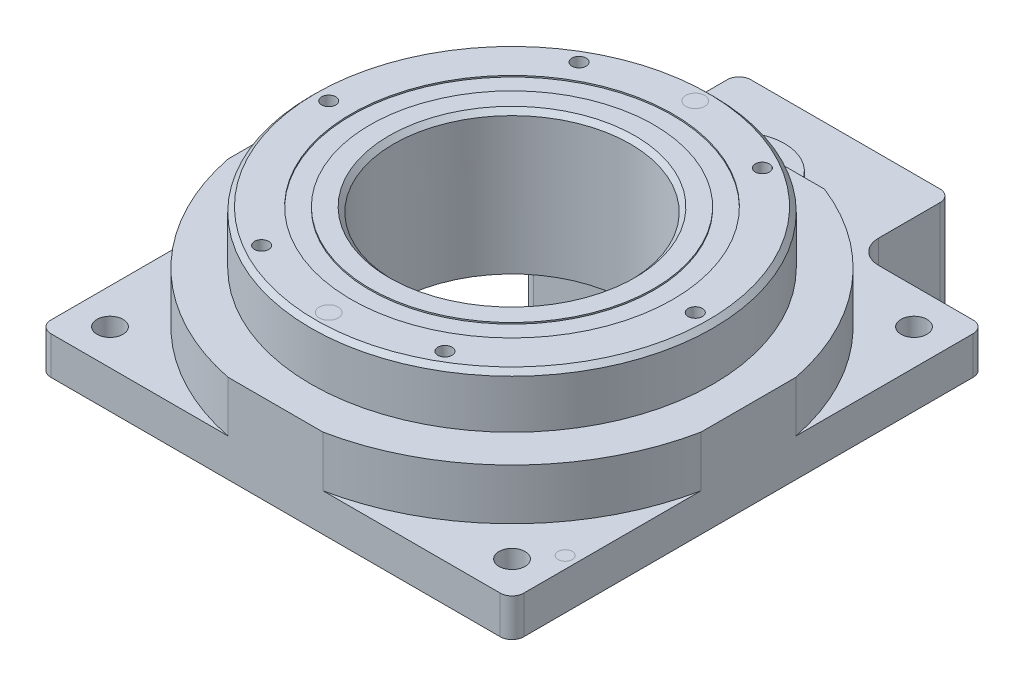
SolidWorks part; units mm, degrees
ref_plane "前视基准面" through (0, 0, 0) normal (0, 0, 1) x (1, 0, 0)
ref_plane "上视基准面" through (0, 0, 0) normal (0, 1, 0) x (1, 0, 0)
ref_plane "右视基准面" through (0, 0, 0) normal (1, 0, 0) x (0, 0, -1)
sketch "草图1" plane through (0, 0, 0) normal (0, 0, 1) x (1, 0, 0)
  line L0 (0, 0) -> (0, 60) construction
  point P3 (85, 60)
  point P4 (50, 60)
  point P5 (0, -53)
  point P6 (0, 37.5)
  point P7 (85, 51.5)
  point P8 (0, 16)
  dimension "D1" = 60
  dimension "D2" = 170
  dimension "D3" = 100
  dimension "D4" = 53
  dimension "D5" = 37.5
  dimension "D6" = 8.5
  dimension "D7" = 16
sketch "草图3" plane through (0, 0, 0) normal (0, 1, 0) x (1, 0, 0)
  line L0 (-141, 45) -> (-141, -45)
  line L1 (100, 100) -> (-100, 100)
  line L2 (100, 100) -> (100, -100)
  line L3 (100, -100) -> (-100, -100)
  line L4 (-100, 100) -> (-100, -100)
  line L5 (100, 100) -> (-100, -100) construction
  line L6 (100, -100) -> (-100, 100) construction
  line L7 (0, 0) -> (-141, 0) construction
  line L8 (-141, 45) -> (-100, 45)
  line L9 (-141, -45) -> (-100, -45)
  line L10 (0, 0) -> (0, 100) construction
  line L11 (-95, 0) -> (-132.1231, 37.1231) construction
  line L12 (0, 0) -> (-100, 8.7489)
  line L13 (0, 0) -> (-100, -8.7489)
  circle A0 centre (85, -85) radius 5.5
  circle A2 centre (-95, 0) radius 52.5 construction
  circle A3 centre (-132.1231, 37.1231) radius 3
  circle A4 centre (-95, 0) radius 9.5
  circle A5 centre (-95, 0) radius 35
  point P0 (0, 0)
  point P12 (85, 85)
  point P13 (85, -85)
  point P14 (-85, 85)
  point P16 (-85, -85)
  point P17 (-102, 10)
  point P18 (-102, -10)
  point P22 (-95, 0)
  dimension "D7" = 11
  dimension "D10" = 105
  dimension "D11" = 45
  dimension "D12" = 6
  dimension "D13" = 19
  dimension "D14" = 70
  dimension "D1" = 200
  dimension "D2" = 241
  dimension "D3" = 90
  dimension "D4" = 85
  dimension "D5" = 20
  dimension "D6" = 39
  dimension "D9" = 95
  dimension "D15" = 10
sketch "草图5" plane through (0, 0, 0) normal (0, 1, 0) x (1, 0, 0)
  circle A0 centre (0, 0) radius 85
extrude "凸台-拉伸1" add sketch "草图5" along normal up to vertex (60 mm away) up to point (50, 60, 0)
sketch "草图6" plane through (0, 0, 0) normal (0, 1, 0) x (1, 0, 0)
  line L1 (100, 100) -> (-100, 100) construction
  line L2 (100, -100) -> (-100, -100) construction
  line L3 (20.0998, 100) -> (-20.0998, 100)
  line L4 (20.0998, -100) -> (-20.0998, -100)
  line L5 (100, 100) -> (100, -100) construction
  line L6 (100, 20.0998) -> (100, -20.0998)
  arc A0 (-20.0998, 100) -> (-20.0998, -100) centre (0, 0) ccw
  arc A1 (20.0998, -100) -> (100, -20.0998) centre (0, 0) ccw
  arc A2 (100, 20.0998) -> (20.0998, 100) centre (0, 0) ccw
  dimension "D1" = 204
extrude "凸台-拉伸2" add sketch "草图6" along normal up to vertex (37.5 mm away) up to point (0, 37.5, 0)
sketch "草图7" plane through (0, 0, 0) normal (0, 1, 0) x (1, 0, 0)
  line L0 (-141, 45) -> (-100, 45) construction
  line L1 (-141, 45) -> (-141, -45) construction
  line L2 (-141, -45) -> (-100, -45) construction
  line L3 (-100, 100) -> (-100, -100) construction
  line L4 (100, -100) -> (-100, -100) construction
  line L5 (100, 100) -> (100, -100) construction
  line L6 (100, 100) -> (-100, 100) construction
  line L7 (-141, 45) -> (-100, 45)
  line L8 (-141, 45) -> (-141, -45)
  line L9 (-141, -45) -> (-100, -45)
  line L10 (-100, 100) -> (-100, 45)
  line L11 (100, -100) -> (-100, -100)
  line L12 (100, 100) -> (100, -100)
  line L13 (100, 100) -> (-100, 100)
  line L14 (-100, -45) -> (-100, -100)
extrude "凸台-拉伸3" add sketch "草图7" along normal up to vertex (16 mm away) up to point (0, 16, 0)
sketch "草图8" plane through (0, 0, 0) normal (0, 1, 0) x (1, 0, 0)
  line L0 (0, 0) -> (-72.5, -95) construction
  line L2 (0, 0) -> (0, -95) construction
  circle A0 centre (85, -85) radius 5.5 construction
  circle A1 centre (85, -85) radius 5.5
  circle A2 centre (-72.5, -95) radius 3 construction
  dimension "D1" = 6
  dimension "D2" = 72.5
  dimension "D3" = 95
extrude "切除-拉伸1" cut sketch "草图8" along normal up to vertex (60 mm away) up to point (85, 60, 0)
pattern_circular "阵列(圆周)1" count 4 over 360 about axis through (0, 0, 0) along (0, 1, 0) of "切除-拉伸1"
sketch "草图11" plane through (0, 0, 0) normal (0, 1, 0) x (1, 0, 0)
  circle A0 centre (0, 0) radius 50
extrude "切除-拉伸5" cut sketch "草图11" along normal up to vertex (60 mm away) up to point (0, 60, 0)
sketch "草图12" plane through (0, 0, 0) normal (0, 1, 0) x (1, 0, 0)
  line L1 (-49, -45) -> (-141, -45)
  line L2 (-49, -45) -> (-49, 45)
  line L3 (-49, 45) -> (-141, 45)
  line L4 (-141, -45) -> (-141, 45)
  line L5 (-49, -45) -> (-141, 45) construction
  line L6 (-49, 45) -> (-141, -45) construction
  point P0 (-95, 0)
extrude "凸台-拉伸4" add sketch "草图12" against normal up to vertex (53 mm away) up to point (0, -53, 0)
fillet "圆角1" radius 5 4 edges at (-100, 8, -100) (100, 8, -100) (100, 8, 100) (-100, 8, 100)
fillet "圆角2" radius 5 4 edges at (-49, -26.5, -45) (-141, -18.5, -45) (-49, -26.5, 45) (-141, -18.5, 45)
sketch "草图14" plane through (0, 0, 0) normal (0, 1, 0) x (1, 0, 0)
  circle A0 centre (-95, 0) radius 20.25
  dimension "D1" = 40.5
extrude "凸台-拉伸5" add sketch "草图14" along normal blind 30
fillet "圆角3" radius 10 2 edges at (-100.0997, 23, -19.5973) (-100.0997, 23, 19.5973)
sketch "草图46" plane through (0, 0, 0) normal (0, 1, 0) x (1, 0, 0)
  line L0 (-95, 45) -> (-95, -45)
  line L1 (-141, 45) -> (-100, 45) construction
  line L2 (-141, -45) -> (-100, -45) construction
  line L3 (-95, 45) -> (-141, 45)
  line L4 (-141, 45) -> (-141, -45)
  line L5 (-141, -45) -> (-95, -45)
extrude "切除-拉伸23" cut sketch "草图46" against normal blind 12 from vertex at 37.5 starting at point (0, 37.5, 0)
sketch "草图13" plane through (0, 0, 0) normal (0, 1, 0) x (1, 0, 0)
  circle A0 centre (-102, 10) radius 1.25
  circle A1 centre (-102, -10) radius 1.25
  dimension "D1" = 2.5
extrude "切除-拉伸6" cut sketch "草图13" against normal blind 4 from surface at 25.5 starting at face at (-101.0689, 25.5, 0)
sketch "草图15" plane through (0, 0, 0) normal (0, 1, 0) x (1, 0, 0)
  line L0 (-54, 40) -> (-136, 40)
  line L1 (-49, -45) -> (-141, -45)
  line L2 (-49, -45) -> (-49, 45)
  line L3 (-49, 45) -> (-141, 45)
  line L4 (-141, -45) -> (-141, 45)
  line L5 (-49, -45) -> (-141, 45) construction
  line L6 (-49, 45) -> (-141, -45) construction
  line L7 (-136, -40) -> (-136, 40)
  line L8 (-54, -40) -> (-136, -40)
  line L9 (-54, -40) -> (-54, 40)
  point P0 (-95, 0)
  dimension "D1" = 5
extrude "切除-拉伸8" cut sketch "草图15" against normal blind 0.01 from offset 25 offset against normal yes
sketch "草图16" plane through (0, 0, 0) normal (0, 1, 0) x (1, 0, 0)
  circle A0 centre (-132.1231, 37.1231) radius 3 construction
  circle A1 centre (-132.1231, 37.1231) radius 3
extrude "切除-拉伸9" cut sketch "草图16" along normal blind 10 from vertex at -53 starting at point (0, -53, 0)
cosmetic thread "装饰螺纹线2" parameters "D2"=6.1
pattern_circular "阵列(圆周)3" count 4 over 360 about axis through (-95, 0, 0) along (0, 1, 0) of "切除-拉伸9"
sketch "草图17" plane through (0, 0, 0) normal (0, 0, 1) x (1, 0, 0)
  point P0 (-85, -41)
  dimension "D1" = 12
sketch "螺钉草图1" plane through (-23.5625, -23.3592, -45) normal (0, 0, -1) x (-1, 0, 0)
  circle A0 centre (61.4375, -17.6408) radius 5 construction
  circle A1 centre (61.4375, -17.6408) radius 5.25
  dimension "D1" = 10
  dimension "D2" = 10.5
extrude "切除-沉孔" cut sketch "螺钉草图1" against normal blind 6.2
sketch "螺钉草图2" plane through (-25, -22, -38.8) normal (0, 0, -1) x (-1, 0, 0)
  circle A0 centre (60, -19) radius 5 construction
  circle A1 centre (60, -19) radius 5
extrude "拉伸-螺钉头" add sketch "螺钉草图2" along normal blind 6
fillet "圆角-螺钉头" radius 0.5 1 edges at (-85, -36, -44.8)
sketch "螺钉草图3" plane through (-25, -22, -44.8) normal (0, 0, -1) x (-1, 0, 0)
  line L1 (61.7898, -15.9) -> (58.2102, -15.9)
  line L2 (58.2102, -15.9) -> (56.4204, -19)
  line L3 (56.4204, -19) -> (58.2102, -22.1)
  line L4 (58.2102, -22.1) -> (61.7898, -22.1)
  line L5 (61.7898, -22.1) -> (63.5796, -19)
  line L6 (63.5796, -19) -> (61.7898, -15.9)
  circle A0 centre (60, -19) radius 3.1 construction
  dimension "D1" = 6.2
extrude "切除-螺钉头" cut sketch "螺钉草图3" against normal blind 3.5
other "沉孔螺钉<1>"
sketch "草图21" plane through (0, 0, 0) normal (0, 1, 0) x (1, 0, 0)
  circle A0 centre (-95, 0) radius 35 construction
  circle A1 centre (-95, 0) radius 35
extrude "切除-拉伸12" cut sketch "草图21" along normal blind 5 from vertex at -53 starting at point (0, -53, 0)
sketch "草图22" plane through (0, 0, 0) normal (0, 1, 0) x (1, 0, 0)
  circle A0 centre (-95, 0) radius 9.5 construction
  circle A1 centre (-95, 0) radius 9.5
extrude "切除-拉伸13" cut sketch "草图22" along normal blind 35 from vertex at -53 starting at point (0, -53, 0)
sketch "草图23" plane through (0, 0, 0) normal (0, 1, 0) x (1, 0, 0)
  line L1 (-132.5, -22.5) -> (-57.5, -22.5) construction
  line L2 (-132.5, -22.5) -> (-132.5, 22.5) construction
  line L3 (-132.5, 22.5) -> (-57.5, 22.5) construction
  line L4 (-57.5, -22.5) -> (-57.5, 22.5) construction
  line L5 (-132.5, -22.5) -> (-57.5, 22.5) construction
  line L6 (-132.5, 22.5) -> (-57.5, -22.5) construction
  point P0 (-95, 0)
  dimension "D1" = 75
  dimension "D2" = 45
sketch "螺钉草图11" plane through (-50.6904, -53, -17.5269) normal (0, -1, 0) x (1, 0, 0)
  circle A0 centre (-81.8096, -4.9731) radius 5 construction
  circle A1 centre (-81.8096, -4.9731) radius 5.25
  dimension "D1" = 10
  dimension "D2" = 10.5
extrude "切除-沉孔1" cut sketch "螺钉草图11" against normal blind 6.2
sketch "螺钉草图21" plane through (-49.5, -46.8, -10) normal (0, -1, 0) x (1, 0, 0)
  circle A0 centre (-83, -12.5) radius 5 construction
  circle A1 centre (-83, -12.5) radius 5
extrude "拉伸-螺钉头1" add sketch "螺钉草图21" along normal blind 6
fillet "圆角-螺钉头1" radius 0.5 1 edges at (-132.5, -52.8, -27.5)
sketch "螺钉草图31" plane through (-49.5, -52.8, -10) normal (0, -1, 0) x (1, 0, 0)
  line L1 (-81.2102, -9.4) -> (-84.7898, -9.4)
  line L2 (-84.7898, -9.4) -> (-86.5796, -12.5)
  line L3 (-86.5796, -12.5) -> (-84.7898, -15.6)
  line L4 (-84.7898, -15.6) -> (-81.2102, -15.6)
  line L5 (-81.2102, -15.6) -> (-79.4204, -12.5)
  line L6 (-79.4204, -12.5) -> (-81.2102, -9.4)
  circle A0 centre (-83, -12.5) radius 3.1 construction
  dimension "D1" = 6.2
extrude "切除-螺钉头1" cut sketch "螺钉草图31" against normal blind 3.5
other "沉孔螺钉<2>"
sketch "螺钉草图12" plane through (-49.117, -53, 10.0796) normal (0, -1, 0) x (1, 0, 0)
  circle A0 centre (-83.383, 12.4204) radius 5 construction
  circle A1 centre (-83.383, 12.4204) radius 5.25
  dimension "D1" = 10
  dimension "D2" = 10.5
extrude "切除-沉孔2" cut sketch "螺钉草图12" against normal blind 6.2
sketch "螺钉草图22" plane through (-49.5, -46.8, 10) normal (0, -1, 0) x (1, 0, 0)
  circle A0 centre (-83, 12.5) radius 5 construction
  circle A1 centre (-83, 12.5) radius 5
extrude "拉伸-螺钉头2" add sketch "螺钉草图22" along normal blind 6
fillet "圆角-螺钉头2" radius 0.5 1 edges at (-132.5, -52.8, 17.5)
sketch "螺钉草图32" plane through (-49.5, -52.8, 10) normal (0, -1, 0) x (1, 0, 0)
  line L1 (-81.2102, 15.6) -> (-84.7898, 15.6)
  line L2 (-84.7898, 15.6) -> (-86.5796, 12.5)
  line L3 (-86.5796, 12.5) -> (-84.7898, 9.4)
  line L4 (-84.7898, 9.4) -> (-81.2102, 9.4)
  line L5 (-81.2102, 9.4) -> (-79.4204, 12.5)
  line L6 (-79.4204, 12.5) -> (-81.2102, 15.6)
  circle A0 centre (-83, 12.5) radius 3.1 construction
  dimension "D1" = 6.2
extrude "切除-螺钉头2" cut sketch "螺钉草图32" against normal blind 3.5
other "沉孔螺钉<3>"
sketch "螺钉草图13" plane through (-14.8755, -53, 9.9062) normal (0, -1, 0) x (1, 0, 0)
  circle A0 centre (-42.6245, 12.5938) radius 5 construction
  circle A1 centre (-42.6245, 12.5938) radius 5.25
  dimension "D1" = 10
  dimension "D2" = 10.5
extrude "切除-沉孔3" cut sketch "螺钉草图13" against normal blind 6.2
sketch "螺钉草图23" plane through (-14.5, -46.8, 10) normal (0, -1, 0) x (1, 0, 0)
  circle A0 centre (-43, 12.5) radius 5 construction
  circle A1 centre (-43, 12.5) radius 5
extrude "拉伸-螺钉头3" add sketch "螺钉草图23" along normal blind 6
fillet "圆角-螺钉头3" radius 0.5 1 edges at (-57.5, -52.8, 17.5)
sketch "螺钉草图33" plane through (-14.5, -52.8, 10) normal (0, -1, 0) x (1, 0, 0)
  line L1 (-41.2102, 15.6) -> (-44.7898, 15.6)
  line L2 (-44.7898, 15.6) -> (-46.5796, 12.5)
  line L3 (-46.5796, 12.5) -> (-44.7898, 9.4)
  line L4 (-44.7898, 9.4) -> (-41.2102, 9.4)
  line L5 (-41.2102, 9.4) -> (-39.4204, 12.5)
  line L6 (-39.4204, 12.5) -> (-41.2102, 15.6)
  circle A0 centre (-43, 12.5) radius 3.1 construction
  dimension "D1" = 6.2
extrude "切除-螺钉头3" cut sketch "螺钉草图33" against normal blind 3.5
other "沉孔螺钉<4>"
sketch "螺钉草图14" plane through (-14.6538, -53, -9.3891) normal (0, -1, 0) x (1, 0, 0)
  circle A0 centre (-42.8462, -13.1109) radius 5 construction
  circle A1 centre (-42.8462, -13.1109) radius 5.25
  dimension "D1" = 10
  dimension "D2" = 10.5
extrude "切除-沉孔4" cut sketch "螺钉草图14" against normal blind 6.2
sketch "螺钉草图24" plane through (-14.5, -46.8, -10) normal (0, -1, 0) x (1, 0, 0)
  circle A0 centre (-43, -12.5) radius 5 construction
  circle A1 centre (-43, -12.5) radius 5
extrude "拉伸-螺钉头4" add sketch "螺钉草图24" along normal blind 6
fillet "圆角-螺钉头4" radius 0.5 1 edges at (-57.5, -52.8, -27.5)
sketch "螺钉草图34" plane through (-14.5, -52.8, -10) normal (0, -1, 0) x (1, 0, 0)
  line L1 (-41.2102, -9.4) -> (-44.7898, -9.4)
  line L2 (-44.7898, -9.4) -> (-46.5796, -12.5)
  line L3 (-46.5796, -12.5) -> (-44.7898, -15.6)
  line L4 (-44.7898, -15.6) -> (-41.2102, -15.6)
  line L5 (-41.2102, -15.6) -> (-39.4204, -12.5)
  line L6 (-39.4204, -12.5) -> (-41.2102, -9.4)
  circle A0 centre (-43, -12.5) radius 3.1 construction
  dimension "D1" = 6.2
extrude "切除-螺钉头4" cut sketch "螺钉草图34" against normal blind 3.5
other "沉孔螺钉<5>"
sketch "草图37" plane through (0, 0, 0) normal (0, 0, 1) x (1, 0, 0)
  line L0 (60, 60) -> (60, 59.4)
  line L1 (85, 60) -> (-85, 60) construction
  line L2 (60, 59.4) -> (68, 59.4)
  line L3 (68, 59.4) -> (68, 60)
  line L4 (68, 60) -> (60, 60)
  line L5 (0, 0) -> (0, 60) construction
  dimension "D1" = 60
  dimension "D2" = 68
  dimension "D3" = 0.6
revolve "切除-旋转1" cut sketch "草图37" angle 360 about L0
sketch "草图38" plane through (0, 0, 0) normal (0, 1, 0) x (1, 0, 0)
  circle A0 centre (0, 0) radius 77.5 construction
  circle A1 centre (0, 77.5) radius 3
  dimension "D1" = 155
  dimension "D2" = 6
extrude "切除-拉伸22" cut sketch "草图38" against normal blind 6 from vertex at 60 starting at point (0, 60, 0)
cosmetic thread "装饰螺纹线1" parameters "D2"=6.1
pattern_circular "阵列(圆周)4" count 6 over 360 about axis through (0, 0, 0) along (0, 1, 0) of "切除-拉伸22"
sketch "草图39" plane through (0, 0, 0) normal (0, 1, 0) x (1, 0, 0)
  circle A0 centre (0, 0) radius 77.5 construction
  circle A1 centre (77.5, 0) radius 4
  circle A2 centre (-77.5, 0) radius 4
  circle A3 centre (0, 0) radius 77.5 construction
  dimension "D2" = 8
split line "分割线1"
sketch "草图40" plane through (0, 0, 0) normal (0, 1, 0) x (1, 0, 0)
  circle A0 centre (0, 0) radius 60 construction
  point P4 (0, -60)
  dimension "D1" = 120
sketch "螺钉草图16" plane through (-3.1746, 0, 35.5922) normal (0, -1, 0) x (1, 0, 0)
  circle A0 centre (3.1746, 24.4078) radius 8 construction
  circle A1 centre (3.1746, 24.4078) radius 8.4
  dimension "D1" = 16
  dimension "D2" = 16.8
extrude "切除-沉孔5" cut sketch "螺钉草图16" against normal blind 9.92
sketch "螺钉草图26" plane through (0, 9.92, 37.2) normal (0, -1, 0) x (1, 0, 0)
  circle A0 centre (0, 22.8) radius 8 construction
  circle A1 centre (0, 22.8) radius 8
extrude "拉伸-螺钉头5" add sketch "螺钉草图26" along normal blind 9.6
fillet "圆角-螺钉头5" radius 0.8 1 edges at (0, 0.32, 52)
sketch "螺钉草图35" plane through (0, 0.32, 37.2) normal (0, -1, 0) x (1, 0, 0)
  line L1 (2.8637, 27.76) -> (-2.8637, 27.76)
  line L2 (-2.8637, 27.76) -> (-5.7273, 22.8)
  line L3 (-5.7273, 22.8) -> (-2.8637, 17.84)
  line L4 (-2.8637, 17.84) -> (2.8637, 17.84)
  line L5 (2.8637, 17.84) -> (5.7273, 22.8)
  line L6 (5.7273, 22.8) -> (2.8637, 27.76)
  circle A0 centre (0, 22.8) radius 4.96 construction
  dimension "D1" = 9.92
extrude "切除-螺钉头5" cut sketch "螺钉草图35" against normal blind 5.6
other "沉孔螺钉<6>"
pattern_circular "阵列(圆周)5" count 6 over 360 about axis through (0, 0, 0) along (0, 1, 0) of "切除-沉孔5", "拉伸-螺钉头5", "圆角-螺钉头5", "切除-螺钉头5"
ref_plane "基准面1" through (0, 51.5, 0) normal (0, 1, 0) x (-1, 0, 0)
sketch "草图43" plane through (0, 51.5, 0) normal (0, 1, 0) x (-1, 0, 0)
  line L0 (84.5676, 8.6535) -> (80.5828, 8.3049)
  line L1 (0, 0) -> (100, 8.7489) construction
  line L4 (80.6918, 7.0596) -> (84.6765, 7.4082)
  line L5 (84.6765, 7.4082) -> (84.5676, 8.6535)
  line L6 (80.5828, 8.3049) -> (80.6918, 7.0596)
  circle A2 centre (0, 0) radius 85 construction
  dimension "D1" = 1.25
  dimension "D2" = 4
revolve "切除-旋转2" cut sketch "草图43" angle 360 about L1
cosmetic thread "装饰螺纹线3" parameters "D2"=2.6
mirror "镜向1" about plane through (0, 0, 0) normal (0, 0, 1) of "切除-旋转2"
chamfer "倒角1" distance 1 angle 45 2 edges at (-95, -53, 35) (-95, -48, 9.5)
chamfer "倒角2" distance 2 angle 45 2 edges at (0, 60, 85) (0, 60, 50)
sketch "草图45" plane through (0, 0, 0) normal (0, 1, 0) x (1, 0, 0)
  line L0 (-72.5, -95) -> (0, 0) construction
  line L1 (0, 0) -> (-72.5, -95) construction
  line L2 (0, 0) -> (72.5, 95) construction
  circle A0 centre (-72.5, -95) radius 3 construction
  circle A1 centre (-72.5, -95) radius 3
  circle A2 centre (72.5, 95) radius 3
split line "分割线2"
move or copy body "实体-移动/复制2" bodies to move or copy 145 copy no rotation origin (-12, 0, 0) rotation axis (0, -1, 0) rotation angle 90
fillet "圆角4" radius 10 2 edges
